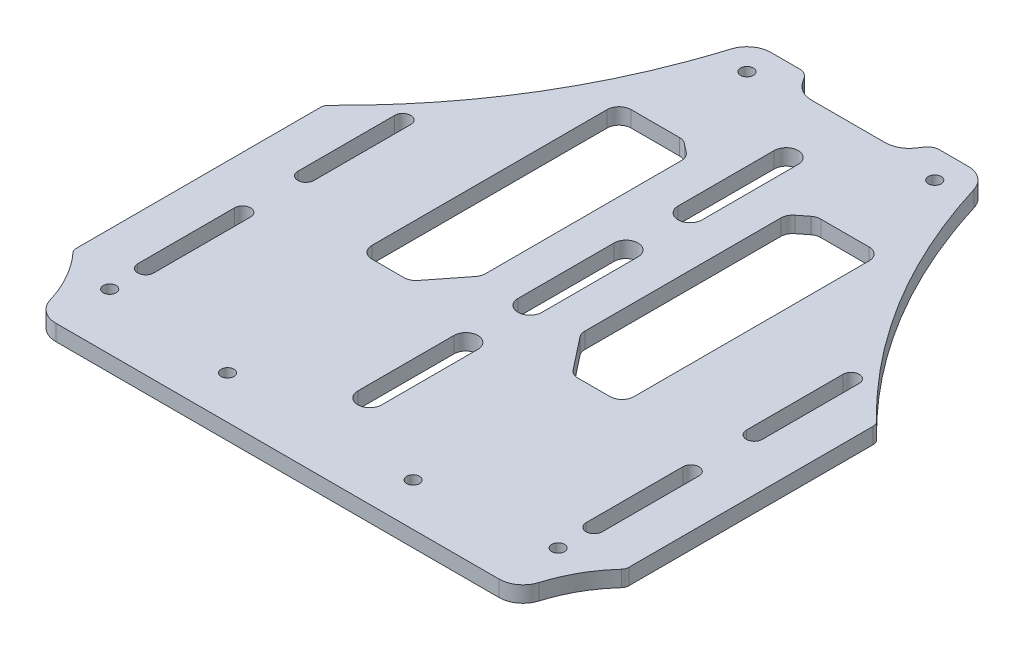
SolidWorks part; units mm, degrees
ref_plane "Front Plane" through (0, 0, 0) normal (0, 0, 1) x (1, 0, 0)
ref_plane "Top Plane" through (0, 0, 0) normal (0, 1, 0) x (1, 0, 0)
ref_plane "Right Plane" through (0, 0, 0) normal (1, 0, 0) x (0, 0, -1)
sketch "Sketch3" plane through (0, 0, 0) normal (0, 1, 0) x (1, 0, 0)
  line L0 (0, -12.0357) -> (0, 11.9643) construction
  line L2 (-75, -2.6883) -> (-75, -48.9987)
  line L4 (75, -2.6883) -> (75, -48.9987)
  line L7 (-3, -12.0357) -> (-3, 11.9643)
  line L8 (3, -12.0357) -> (3, 11.9643)
  line L9 (0, 27.9643) -> (0, 51.9643) construction
  line L10 (-3, 27.9643) -> (-3, 51.9643)
  line L11 (3, 27.9643) -> (3, 51.9643)
  line L12 (0, -52.0357) -> (0, -28.0357) construction
  line L13 (-3, -52.0357) -> (-3, -28.0357)
  line L14 (3, -52.0357) -> (3, -28.0357)
  line L15 (56, -12) -> (56, 12.1843) construction
  line L16 (54, -12) -> (54, 12.1843)
  line L17 (58, -12) -> (58, 12.1843)
  line L18 (56, -52) -> (56, -27.8157) construction
  line L19 (54, -52) -> (54, -27.8157)
  line L20 (58, -52) -> (58, -27.8157)
  line L24 (16, 54.9643) -> (34.4753, 54.9643) construction
  line L25 (16, 54.9643) -> (23.4565, 65.6133) construction
  line L26 (0, -55.0357) -> (0, 0.0921) construction
  line L27 (-56, -12) -> (-56, 12.1843) construction
  line L28 (-54, -12) -> (-54, 12.1843)
  line L29 (-58, -12) -> (-58, 12.1843)
  line L30 (-56, -52) -> (-56, -27.8157) construction
  line L31 (-54, -52) -> (-54, -27.8157)
  line L32 (-58, -52) -> (-58, -27.8157)
  line L33 (17.4821, 72.7744) -> (24.6157, 72.7744)
  line L36 (0, 54.9643) -> (16, 54.9643) construction
  line L37 (13.5592, 40.5575) -> (15.7949, 42.3142)
  line L38 (0, 0.0921) -> (12.4127, 0.0921) construction
  line L39 (17.6484, 42.9552) -> (29.7223, 42.9552)
  line L41 (29.7223, -21.7644) -> (21.7225, -21.7644)
  line L42 (19.3635, -20.6179) -> (13.0538, -12.5875)
  line L43 (12.4127, -10.734) -> (12.4127, 38.1986)
  line L44 (32.7223, 39.9552) -> (32.7223, -18.7644)
  line L45 (-32.7223, 39.9552) -> (-32.7223, -18.7644)
  line L46 (-12.4127, -10.734) -> (-12.4127, 38.1986)
  line L47 (-19.3635, -20.6179) -> (-13.0538, -12.5875)
  line L48 (-29.7223, -21.7644) -> (-21.7225, -21.7644)
  line L49 (-17.6484, 42.9552) -> (-29.7223, 42.9552)
  line L50 (-13.5592, 40.5575) -> (-15.7949, 42.3142)
  line L52 (-15.0037, 71.4649) -> (-14.106, 70.1487)
  line L53 (-9.1492, 67.5295) -> (-5.712, 67.5295)
  line L56 (9.1492, 67.5295) -> (5.712, 67.5295)
  line L57 (15.0037, 71.4649) -> (14.106, 70.1487)
  line L67 (23.4565, -65.429) -> (23.4565, -65.249) construction
  line L68 (-24.6157, 72.7744) -> (-17.4821, 72.7744)
  line L69 (23.4565, -65.9606) -> (23.4565, -63.429) construction
  line L70 (-3, 3.4) -> (3, -3.4) construction
  line L71 (-55.3343, -75.0946) -> (55.3343, -75.0946)
  line L72 (-5.712, 67.5295) -> (5.712, 67.5295)
  line L73 (-3, -3.4) -> (3, 3.4) construction
  arc A0 (-3, -12.0357) -> (3, -12.0357) centre (0, -12.0357) ccw
  arc A1 (3, 11.9643) -> (-3, 11.9643) centre (0, 11.9643) ccw
  arc A2 (-3, 27.9643) -> (3, 27.9643) centre (0, 27.9643) ccw
  arc A3 (3, 51.9643) -> (-3, 51.9643) centre (0, 51.9643) ccw
  arc A4 (-3, -52.0357) -> (3, -52.0357) centre (0, -52.0357) ccw
  arc A5 (3, -28.0357) -> (-3, -28.0357) centre (0, -28.0357) ccw
  arc A7 (54, -12) -> (58, -12) centre (56, -12) ccw
  arc A8 (58, 12.1843) -> (54, 12.1843) centre (56, 12.1843) ccw
  arc A9 (54, -52) -> (58, -52) centre (56, -52) ccw
  arc A10 (58, -27.8157) -> (54, -27.8157) centre (56, -27.8157) ccw
  circle A14 centre (16, 54.9643) radius 1.6
  circle A15 centre (23.4565, 65.6133) radius 1.6
  arc A16 (-54, -12) -> (-58, -12) centre (-56, -12) cw
  arc A17 (-58, 12.1843) -> (-54, 12.1843) centre (-56, 12.1843) cw
  arc A18 (-54, -52) -> (-58, -52) centre (-56, -52) cw
  arc A19 (-58, -27.8157) -> (-54, -27.8157) centre (-56, -27.8157) cw
  circle A22 centre (-23.4565, 65.6133) radius 1.6
  circle A26 centre (-56, -61) radius 1.6
  circle A27 centre (56, -61) radius 1.6
  circle A30 centre (-56, -61) radius 1.6
  circle A36 centre (23.1686, -64.3867) radius 1.6
  circle A39 centre (-23.1686, -64.3867) radius 1.6
  arc A40 (-72.7546, -53.6787) -> (-75, -48.9987) centre (-69, -48.9987) cw
  arc A41 (-61.0804, -70.8216) -> (-55.3343, -75.0946) centre (-55.3343, -69.0946) ccw
  arc A42 (72.7546, -53.6787) -> (75, -48.9987) centre (69, -48.9987) ccw
  arc A43 (61.0804, -70.8216) -> (55.3343, -75.0946) centre (55.3343, -69.0946) cw
  arc A44 (30.3494, 68.542) -> (24.6157, 72.7744) centre (24.6157, 66.7744) ccw
  arc A45 (73.0291, 1.7576) -> (75, -2.6883) centre (69, -2.6883) cw
  arc A46 (-73.0291, 1.7576) -> (-75, -2.6883) centre (-69, -2.6883) ccw
  arc A47 (-30.3494, 68.542) -> (-24.6157, 72.7744) centre (-24.6157, 66.7744) cw
  arc A48 (9.1492, 67.5295) -> (14.106, 70.1487) centre (9.1492, 73.5295) ccw
  arc A49 (-14.106, 70.1487) -> (-9.1492, 67.5295) centre (-9.1492, 73.5295) ccw
  arc A52 (15.0037, 71.4649) -> (17.4821, 72.7744) centre (17.4821, 69.7744) cw
  arc A53 (-15.0037, 71.4649) -> (-17.4821, 72.7744) centre (-17.4821, 69.7744) ccw
  arc A54 (32.7223, -18.7644) -> (29.7223, -21.7644) centre (29.7223, -18.7644) cw
  arc A55 (-32.7223, -18.7644) -> (-29.7223, -21.7644) centre (-29.7223, -18.7644) ccw
  arc A56 (-19.3635, -20.6179) -> (-21.7225, -21.7644) centre (-21.7225, -18.7644) cw
  arc A57 (-12.4127, -10.734) -> (-13.0538, -12.5875) centre (-15.4127, -10.734) cw
  arc A58 (21.7225, -21.7644) -> (19.3635, -20.6179) centre (21.7225, -18.7644) cw
  arc A59 (13.0538, -12.5875) -> (12.4127, -10.734) centre (15.4127, -10.734) cw
  arc A60 (-17.6484, 42.9552) -> (-15.7949, 42.3142) centre (-17.6484, 39.9552) cw
  arc A61 (-12.4127, 38.1986) -> (-13.5592, 40.5575) centre (-15.4127, 38.1986) ccw
  arc A62 (13.5592, 40.5575) -> (12.4127, 38.1986) centre (15.4127, 38.1986) ccw
  arc A63 (15.7949, 42.3142) -> (17.6484, 42.9552) centre (17.6484, 39.9552) cw
  arc A64 (29.7223, 42.9552) -> (32.7223, 39.9552) centre (29.7223, 39.9552) cw
  arc A65 (-32.7223, 39.9552) -> (-29.7223, 42.9552) centre (-29.7223, 39.9552) cw
  spline S0 degree 3 poles (-73.0291, 1.7576) (-61.0443, 12.619) (-44.265, 33.3058) (-33.6646, 57.7883) (-30.3494, 68.542) knots 0.029324 0.029324 0.029324 0.029324 0.569458 0.950407 0.950407 0.950407 0.950407
  spline S1 degree 3 poles (73.0291, 1.7576) (61.0443, 12.619) (44.265, 33.3058) (33.6646, 57.7883) (30.3494, 68.542) knots 0.029324 0.029324 0.029324 0.029324 0.569458 0.950407 0.950407 0.950407 0.950407
  spline S2 degree 3 poles (-72.7546, -53.6787) (-69.1555, -56.5662) (-64.5992, -61.8323) (-61.8439, -68.2812) (-61.0804, -70.8216) knots 0.094602 0.094602 0.094602 0.094602 0.56784 0.847958 0.847958 0.847958 0.847958
  spline S3 degree 3 poles (72.7546, -53.6787) (69.1555, -56.5662) (64.5992, -61.8323) (61.8439, -68.2812) (61.0804, -70.8216) knots 0.094602 0.094602 0.094602 0.094602 0.56784 0.847958 0.847958 0.847958 0.847958
  point P0 (0, 0)
  point P8 (0, -0.0357)
  point P16 (0, 39.9643)
  point P23 (0, -40.0357)
  point P31 (56, 0.0921)
  point P40 (56, -39.9079)
  point P45 (12.3196, 67.5295)
  point P47 (56, 40)
  point P50 (-12.3196, 67.5295)
  point P61 (-56, 0.0921)
  point P68 (-56, -39.9079)
  point P73 (32.7223, -21.7644)
  point P75 (-56, 40)
  point P76 (4.712, 67.5295)
  point P85 (-4.712, 67.5295)
  point P95 (-32.7223, -21.7644)
  point P112 (-20.2644, -21.7644)
  point P122 (15.897, 72.7744)
  point P130 (-12.4127, -11.7716)
  point P134 (20.2644, -21.7644)
  point P153 (-4.712, 72.7744)
  point P159 (12.4127, -11.7716)
  point P162 (4.712, 72.7744)
  point P167 (-16.6108, 42.9552)
  point P170 (-12.4127, 39.6567)
  point P173 (12.4127, 39.6567)
  point P176 (16.6108, 42.9552)
  point P179 (32.7223, 42.9552)
  point P182 (-32.7223, 42.9552)
  dimension "D4" = 24
  dimension "D7" = 16
  dimension "D14" = 3
  dimension "D15" = 3
  dimension "D16" = 3.2
  dimension "D20" = 3.2
  dimension "D8" = 6
  dimension "D17" = 23.1686
  dimension "D21" = 130
  dimension "D23" = 3.2
  dimension "D25" = 3.2
  dimension "D13" = 6
  dimension "D3" = 6
  dimension "D9" = 2
  dimension "D10" = 4
  dimension "D11" = 51
  dimension "D12" = 2
  dimension "D18" = 55
  dimension "D19" = 13
  dimension "D22" = 1
  dimension "D24" = 130
  dimension "D26" = 23.1686
  dimension "D5" = 2
  dimension "D6" = 2
extrude "Boss-Extrude1" add sketch "Sketch3" along normal blind 4
sketch "Sketch5" plane through (0, 4, 0) normal (0, 1, 0) x (1, 0, 0)
  line L0 (15.2453, 58.6153) -> (12.1569, 54.2229)
  line L1 (12.1569, 54.2229) -> (18.3337, 47.0166)
  line L2 (18.3337, 47.0166) -> (24.0024, 55.0788)
  line L3 (24.0024, 55.0788) -> (15.2453, 58.6153)
extrude "Boss-Extrude2" add sketch "Sketch5" against normal up to surface (4 mm away) up to face at (0, 0, -12.3773)
sketch "Sketch6" plane through (0, 4, 0) normal (0, 1, 0) x (1, 0, 0)
  line L0 (63.5132, 11.1299) -> (63.5132, -64.8042)
  line L3 (-63.5132, 11.1299) -> (-63.5132, -64.8042)
  spline S0 degree 3 poles (73.0291, 1.7576) (61.0443, 12.619) (44.265, 33.3058) (33.6646, 57.7883) (30.3494, 68.542) knots 0.029324 0.029324 0.029324 0.029324 0.569458 0.950407 0.950407 0.950407 0.950407 construction
  spline S1 degree 3 poles (72.7546, -53.6787) (69.1555, -56.5662) (64.5992, -61.8323) (61.8439, -68.2812) (61.0804, -70.8216) knots 0.094602 0.094602 0.094602 0.094602 0.56784 0.847958 0.847958 0.847958 0.847958 construction
sketch "Sketch7" plane through (0, 4, 0) normal (0, 1, 0) x (1, 0, 0)
  line L0 (44.8504, 35.8671) -> (44.8504, -75.0946)
  line L1 (-55.3343, -75.0946) -> (55.3343, -75.0946) construction
  line L2 (0, 0) -> (0, -80.7274) construction
  line L3 (-44.8504, 35.8671) -> (-44.8504, -75.0946)
  line L7 (-69, 5.5353) -> (-69, -57.1229)
  line L10 (69, 5.5353) -> (69, -57.1229)
  line L12 (75, -48.9987) -> (75, -2.6883)
  line L13 (24.6157, 72.7744) -> (17.4821, 72.7744)
  line L14 (15.0037, 71.4649) -> (14.106, 70.1487)
  line L15 (9.1492, 67.5295) -> (-9.1492, 67.5295)
  line L16 (-14.106, 70.1487) -> (-15.0037, 71.4649)
  line L17 (-17.4821, 72.7744) -> (-24.6157, 72.7744)
  line L18 (-75, -2.6883) -> (-75, -48.9987)
  line L19 (-55.3343, -75.0946) -> (55.3343, -75.0946)
  line L20 (75, -48.9987) -> (75, -2.6883)
  line L26 (-75, -2.6883) -> (-75, -48.9987)
  arc A12 (72.7546, -53.6787) -> (75, -48.9987) centre (69, -48.9987) ccw
  arc A13 (75, -2.6883) -> (73.0291, 1.7576) centre (69, -2.6883) ccw
  arc A14 (30.3494, 68.542) -> (24.6157, 72.7744) centre (24.6157, 66.7744) ccw
  arc A15 (17.4821, 72.7744) -> (15.0037, 71.4649) centre (17.4821, 69.7744) ccw
  arc A16 (9.1492, 67.5295) -> (14.106, 70.1487) centre (9.1492, 73.5295) ccw
  arc A17 (-14.106, 70.1487) -> (-9.1492, 67.5295) centre (-9.1492, 73.5295) ccw
  arc A18 (-15.0037, 71.4649) -> (-17.4821, 72.7744) centre (-17.4821, 69.7744) ccw
  arc A19 (-24.6157, 72.7744) -> (-30.3494, 68.542) centre (-24.6157, 66.7744) ccw
  arc A20 (-73.0291, 1.7576) -> (-75, -2.6883) centre (-69, -2.6883) ccw
  arc A21 (-75, -48.9987) -> (-72.7546, -53.6787) centre (-69, -48.9987) ccw
  arc A22 (-61.0804, -70.8216) -> (-55.3343, -75.0946) centre (-55.3343, -69.0946) ccw
  arc A23 (55.3343, -75.0946) -> (61.0804, -70.8216) centre (55.3343, -69.0946) ccw
  arc A24 (72.7546, -53.6787) -> (75, -48.9987) centre (69, -48.9987) ccw
  arc A25 (75, -2.6883) -> (73.0291, 1.7576) centre (69, -2.6883) ccw
  arc A32 (-73.0291, 1.7576) -> (-75, -2.6883) centre (-69, -2.6883) ccw
  arc A33 (-75, -48.9987) -> (-72.7546, -53.6787) centre (-69, -48.9987) ccw
  spline S0 degree 3 poles (73.0291, 1.7576) (61.0443, 12.619) (44.265, 33.3058) (33.6646, 57.7883) (30.3494, 68.542) knots 0.029324 0.029324 0.029324 0.029324 0.569458 0.950407 0.950407 0.950407 0.950407 construction
  spline S3 degree 3 poles (3021.7843, 465.0791) (1136.117, 6.5513) (-770.013, -454.3904) (566.0547, 1076.3248) (2333.3908, 1894.8531) knots -9.873818 -9.873818 -9.873818 -9.873818 0.569458 11.225273 11.225273 11.225273 11.225273 only from (73.0291, 1.7576) to (30.3494, 68.542)
  spline S4 degree 3 poles (73.0291, 1.7576) (71.658, 3.0002) (70.315, 4.2594) (69, 5.5353) knots 0.029324 0.029324 0.029324 0.029324 0.091117 0.091117 0.091117 0.091117
  spline S5 degree 3 poles (2856.3524, 770.9348) (504.8467, -644.7651) (-544.3393, 349.5904) (867.8945, -272.5846) (3040.7242, 300.5993) knots -12.929335 -12.929335 -12.929335 -12.929335 0.374721 14.921321 14.921321 14.921321 14.921321 only from (61.0804, -70.8216) to (72.7546, -53.6787)
  spline S6 degree 3 poles (1072.9167, 16.6264) (461.6811, -99.7086) (-213.12, -115.9105) (132.5942, 494.7823) (613.4043, 880.9686) knots -5.296654 -5.296654 -5.296654 -5.296654 0.569458 6.540676 6.540676 6.540676 6.540676 only from (73.0291, 1.7576) to (30.3494, 68.542)
  spline S7 degree 3 poles (-613.4079, 880.9716) (-132.595, 494.7838) (213.1199, -115.9088) (-461.6774, -99.7087) (-1072.9067, 16.6245) knots -5.560961 -5.560961 -5.560961 -5.560961 0.410273 6.276353 6.276353 6.276353 6.276353 only from (-30.3494, 68.542) to (-73.0291, 1.7576)
  spline S8 degree 3 poles (-3040.6998, 300.5928) (-867.889, -272.5822) (544.342, 349.5906) (-504.8539, -644.7719) (-2856.4028, 770.9651) knots -13.978706 -13.978706 -13.978706 -13.978706 0.56784 13.87199 13.87199 13.87199 13.87199 only from (-72.7546, -53.6787) to (-61.0804, -70.8216)
  spline S9 degree 3 poles (69, -57.1229) (70.1479, -55.9135) (71.399, -54.7663) (72.7546, -53.6787) knots 0.669711 0.669711 0.669711 0.669711 0.847958 0.847958 0.847958 0.847958
  spline S10 degree 3 poles (-3021.7843, 465.0791) (-1136.117, 6.5513) (770.013, -454.3904) (-566.0547, 1076.3248) (-2333.3908, 1894.8531) knots -9.873818 -9.873818 -9.873818 -9.873818 0.569458 11.225273 11.225273 11.225273 11.225273 only from (-73.0291, 1.7576) to (-30.3494, 68.542)
  spline S11 degree 3 poles (-73.0291, 1.7576) (-71.658, 3.0002) (-70.315, 4.2594) (-69, 5.5353) knots 0.029324 0.029324 0.029324 0.029324 0.091117 0.091117 0.091117 0.091117
  spline S12 degree 3 poles (-72.7546, -53.6787) (-71.399, -54.7663) (-70.1479, -55.9135) (-69, -57.1229) knots 0.094602 0.094602 0.094602 0.094602 0.272849 0.272849 0.272849 0.272849
  point P13 (-63.5132, 11.1299)
  point P38 (0, 0)
  dimension "D1" = 0
  dimension "D2" = 0
  dimension "D3" = 0
extrude "Cut-Extrude1" cut sketch "Sketch7" against normal through all both and the other way through all contours A33 S12 L7 S11 A32 L26 | L10 S9 A24 L20 A25 S4
fillet "Fillet1" radius 2 1 edges
fillet "Fillet2" radius 2 3 edges
sketch "Sketch8" plane through (0, 0, 0) normal (0, -1, 0) x (1, 0, 0)
  line L0 (-54, 52) -> (-54, -33.1828) construction
  line L1 (54, 52) -> (54, -33.1828) construction
